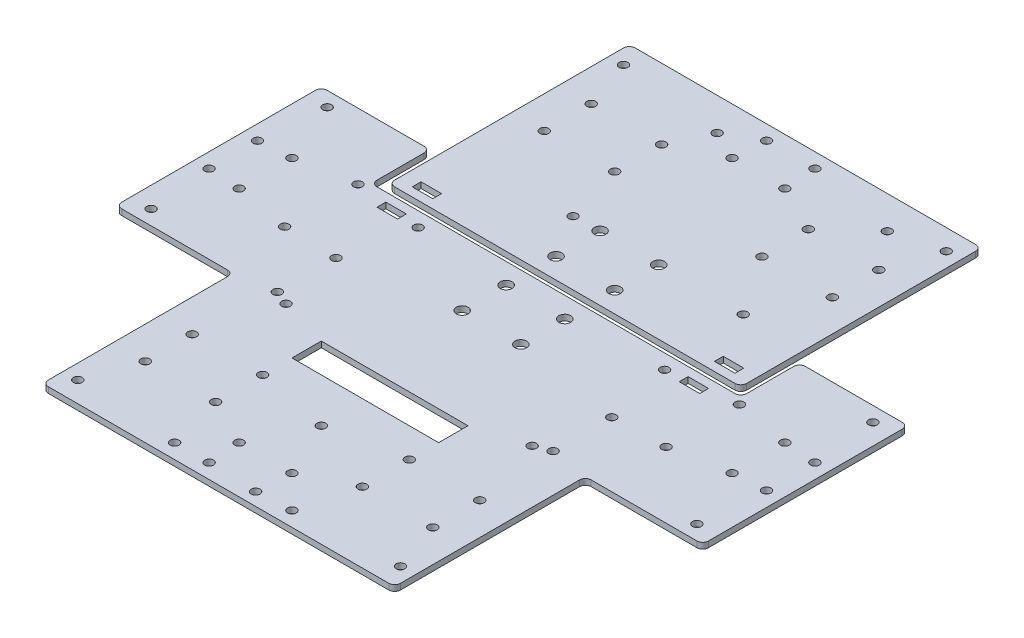
SolidWorks part; units mm, degrees
ref_plane "前视基准面" through (0, 0, 0) normal (0, 0, 1) x (1, 0, 0)
ref_plane "上视基准面" through (0, 0, 0) normal (0, 1, 0) x (1, 0, 0)
ref_plane "右视基准面" through (0, 0, 0) normal (1, 0, 0) x (0, 0, -1)
sketch "草图1" plane through (0, 0, 0) normal (0, 1, 0) x (1, 0, 0)
  line L1 (-97.8773, 105.9195) -> (102.1227, 105.9195)
  line L2 (-97.8773, 105.9195) -> (-97.8773, -94.0805)
  line L3 (-97.8773, -94.0805) -> (102.1227, -94.0805)
  line L4 (102.1227, 105.9195) -> (102.1227, -94.0805)
  dimension "D1" = 200
  dimension "D2" = 200
extrude "底板" add sketch "草图1" along normal blind 2
sketch "草图2" plane through (0, 2, 0) normal (0, 1, 0) x (1, 0, 0)
  line L1 (-97.8773, 105.9195) -> (-57.8773, 105.9195)
  line L2 (-97.8773, 105.9195) -> (-97.8773, 40.9195)
  line L3 (-97.8773, 40.9195) -> (-57.8773, 40.9195)
  line L4 (-57.8773, 105.9195) -> (-57.8773, 40.9195)
  line L9 (102.1227, 105.9195) -> (62.1227, 105.9195)
  line L10 (102.1227, 105.9195) -> (102.1227, 40.9195)
  line L11 (102.1227, 40.9195) -> (62.1227, 40.9195)
  line L12 (62.1227, 105.9195) -> (62.1227, 40.9195)
  line L13 (102.1227, -94.0805) -> (62.1227, -94.0805)
  line L14 (102.1227, -94.0805) -> (102.1227, -29.0805)
  line L15 (102.1227, -29.0805) -> (62.1227, -29.0805)
  line L16 (62.1227, -94.0805) -> (62.1227, -29.0805)
  line L17 (-97.8773, -94.0805) -> (-57.8773, -94.0805)
  line L18 (-97.8773, -94.0805) -> (-97.8773, -29.0805)
  line L19 (-97.8773, -29.0805) -> (-57.8773, -29.0805)
  line L20 (-57.8773, -94.0805) -> (-57.8773, -29.0805)
  dimension "D1" = 65
  dimension "D2" = 40
extrude "麦轮挖空" cut sketch "草图2" against normal blind 2
sketch "草图3" plane through (0, 2, 0) normal (0, 1, 0) x (1, 0, 0)
  line L0 (62.1227, 105.9195) -> (62.1227, 40.9195) construction
  line L1 (62.1227, 105.9195) -> (-57.8773, 105.9195) construction
  line L3 (-57.8773, 40.9195) -> (-57.8773, 105.9195) construction
  line L4 (-57.8773, -94.0805) -> (-57.8773, -29.0805) construction
  line L5 (-57.8773, -94.0805) -> (62.1227, -94.0805) construction
  line L6 (62.1227, -29.0805) -> (62.1227, -94.0805) construction
  circle A0 centre (-46.8773, 81.9195) radius 1.5
  circle A1 centre (-22.8773, 81.9195) radius 1.5
  circle A2 centre (-46.8773, 65.9195) radius 1.5
  circle A3 centre (-22.8773, 65.9195) radius 1.5
  circle A4 centre (-46.8773, -54.0805) radius 1.5
  circle A5 centre (-22.8773, -54.0805) radius 1.5
  circle A6 centre (-46.8773, -70.0805) radius 1.5
  circle A7 centre (-22.8773, -70.0805) radius 1.5
  circle A8 centre (27.1227, -54.0805) radius 1.5
  circle A9 centre (51.1227, -54.0805) radius 1.5
  circle A10 centre (27.1227, -70.0805) radius 1.5
  circle A11 centre (51.1227, -70.0805) radius 1.5
  circle A12 centre (27.1227, 81.9195) radius 1.5
  circle A13 centre (51.1227, 81.9195) radius 1.5
  circle A14 centre (27.311, 65.9206) radius 1.5
  circle A15 centre (51.311, 65.9206) radius 1.5
  dimension "D1" = 24
  dimension "D2" = 16
  dimension "D3" = 16
  dimension "D4" = 24
  dimension "D5" = 11
  dimension "D6" = 24
  dimension "D7" = 16
  dimension "D8" = 16
  dimension "D9" = 11
  dimension "D10" = 24
  dimension "D11" = 24
  dimension "D12" = 16
  dimension "D13" = 16
  dimension "D14" = 11
  dimension "D15" = 24
  dimension "D16" = 24
  dimension "D17" = 24
  dimension "D18" = 16
  dimension "D19" = 16
  dimension "D20" = 24
  dimension "D21" = 11
  dimension "D22" = 24
  dimension "D23" = 24
  dimension "D24" = 24
extrude "电机支架钻孔" cut sketch "草图3" against normal blind 2
sketch "草图4" plane through (0, 2, 0) normal (0, 1, 0) x (1, 0, 0)
  line L0 (62.1227, 105.9195) -> (-57.8773, 105.9195) construction
  line L1 (-97.8773, 40.9195) -> (-97.8773, -29.0805) construction
  line L2 (-57.8773, -94.0805) -> (62.1227, -94.0805) construction
  line L3 (102.1227, -29.0805) -> (102.1227, 40.9195) construction
  circle A0 centre (-6.8773, 89.9195) radius 1.5
  circle A1 centre (11.1227, 89.9195) radius 1.5
  circle A2 centre (-6.8773, -78.0805) radius 1.5
  circle A3 centre (11.1227, -78.0805) radius 1.5
  circle A4 centre (-81.8773, 14.9195) radius 1.5
  circle A5 centre (-81.8773, -3.0805) radius 1.5
  circle A6 centre (86.1227, 14.9195) radius 1.5
  circle A7 centre (86.1227, -3.0805) radius 1.5
  point P4 (-97.8773, 5.9195)
  point P9 (2.1227, 105.9195)
  point P14 (2.1227, -94.0805)
  point P29 (102.1227, 5.9195)
  dimension "D1" = 18
  dimension "D8" = 18
  dimension "D2" = 16
  dimension "D3" = 16
  dimension "D4" = 9
  dimension "D5" = 18
  dimension "D6" = 9
  dimension "D7" = 16
  dimension "D9" = 16
  dimension "D10" = 16
  dimension "D11" = 9
  dimension "D12" = 18
  dimension "D13" = 16
  dimension "D14" = 9
  dimension "D15" = 16
extrude "巡线钻孔" cut sketch "草图4" against normal blind 2
sketch "草图5" plane through (0, 2, 0) normal (0, 1, 0) x (1, 0, 0)
  line L0 (-57.8773, -94.0805) -> (62.1227, -94.0805) construction
  line L1 (-57.8773, -94.0805) -> (-57.8773, -29.0805) construction
  line L2 (62.1227, -29.0805) -> (62.1227, -94.0805) construction
  line L3 (62.1227, 105.9195) -> (62.1227, 40.9195) construction
  line L4 (62.1227, 105.9195) -> (-57.8773, 105.9195) construction
  line L7 (-57.8773, 40.9195) -> (-57.8773, 105.9195) construction
  line L8 (-97.8773, 40.9195) -> (-57.8773, 40.9195) construction
  line L9 (-97.8773, 40.9195) -> (-97.8773, -29.0805) construction
  line L10 (102.1227, -29.0805) -> (102.1227, 40.9195) construction
  line L11 (62.1227, 40.9195) -> (102.1227, 40.9195) construction
  line L12 (102.1227, -29.0805) -> (62.1227, -29.0805) construction
  line L13 (-57.8773, -29.0805) -> (-97.8773, -29.0805) construction
  circle A0 centre (-52.8773, -87.0805) radius 1.5
  circle A1 centre (57.1227, -87.0805) radius 1.5
  circle A2 centre (57.1227, 98.9195) radius 1.5
  circle A3 centre (-52.8773, 98.9195) radius 1.5
  circle A4 centre (-90.8773, 35.9195) radius 1.5
  circle A5 centre (-90.8773, -24.0805) radius 1.5
  circle A6 centre (95.1227, 35.9195) radius 1.5
  circle A7 centre (95.1227, -24.0805) radius 1.5
  dimension "D1" = 7
  dimension "D5" = 5
  dimension "D7" = 7
  dimension "D9" = 5
  dimension "D17" = 3
  dimension "D2" = 5
  dimension "D3" = 7
  dimension "D4" = 5
  dimension "D6" = 7
  dimension "D8" = 5
  dimension "D10" = 7
  dimension "D11" = 7
  dimension "D12" = 7
  dimension "D13" = 7
  dimension "D14" = 5
  dimension "D15" = 5
  dimension "D16" = 5
extrude "保险杠支架钻孔" cut sketch "草图5" against normal blind 10
sketch "草图7" plane through (0, 2, 0) normal (0, 1, 0) x (1, 0, 0)
  line L0 (62.1227, 105.9195) -> (-57.8773, 105.9195) construction
  circle A0 centre (-7.8773, 45.9195) radius 2
  circle A1 centre (-7.8773, 30.9195) radius 2
  circle A2 centre (-7.8773, 13.9195) radius 2
  circle A3 centre (-7.8773, -1.0805) radius 2
  circle A4 centre (12.1227, 45.9195) radius 2
  circle A5 centre (12.1227, 30.9195) radius 2
  circle A6 centre (12.1227, 13.9195) radius 2
  circle A7 centre (12.1227, -1.0805) radius 2
  point P19 (2.1227, 105.9195)
  dimension "D1" = 20
  dimension "D5" = 15
  dimension "D6" = 15
  dimension "D7" = 17
  dimension "D8" = 17
  dimension "D9" = 4
  dimension "D10" = 15
  dimension "D11" = 15
  dimension "D2" = 20
  dimension "D3" = 20
  dimension "D4" = 20
  dimension "D12" = 10
  dimension "D13" = 60
extrude "悬挂钻孔" cut sketch "草图7" against normal blind 10
sketch "草图8" plane through (0, 2, 0) normal (0, 1, 0) x (1, 0, 0)
  line L0 (-57.8773, 40.9195) -> (-57.8773, 23.9195)
  line L1 (-57.8773, 23.9195) -> (62.1227, 23.9195)
  line L2 (62.1227, 23.9195) -> (62.1227, 40.9195)
  line L3 (-57.8773, 40.9195) -> (-60.8773, 40.9195)
  line L4 (-97.8773, 40.9195) -> (-57.8773, 40.9195) construction
  line L5 (-60.8773, 40.9195) -> (-60.8773, 20.9195)
  line L6 (-60.8773, 20.9195) -> (65.1227, 20.9195)
  line L7 (65.1227, 20.9195) -> (65.1227, 40.9195)
  line L8 (62.1227, 40.9195) -> (102.1227, 40.9195) construction
  line L9 (65.1227, 40.9195) -> (62.1227, 40.9195)
  circle A0 centre (-7.8773, 30.9195) radius 2 construction
  dimension "D1" = 7
  dimension "D2" = 3
  dimension "D3" = 3
  dimension "D4" = 3
extrude "悬挂开槽" cut sketch "草图8" against normal blind 10
fillet "主板圆角" radius 2 12 edges at (-97.8773, 1, -40.9195) (-60.8773, 1, -40.9195) (-60.8773, 1, -20.9195) (65.1227, 1, -20.9195) (65.1227, 1, -40.9195) (102.1227, 1, -40.9195) (102.1227, 1, 29.0805) (62.1227, 1, 29.0805) (62.1227, 1, 94.0805) (-57.8773, 1, 94.0805) (-57.8773, 1, 29.0805) (-97.8773, 1, 29.0805)
fillet "小板圆角" radius 2 4 edges at (62.1227, 1, -23.9195) (-57.8773, 1, -23.9195) (-57.8773, 1, -105.9195) (62.1227, 1, -105.9195)
sketch "草图11" plane through (0, 2, 0) normal (0, 1, 0) x (1, 0, 0)
  line L0 (-55.8773, -94.0805) -> (60.1227, -94.0805) construction
  line L2 (62.1227, -31.0805) -> (62.1227, -92.0805) construction
  line L3 (-57.8773, -92.0805) -> (-57.8773, -31.0805) construction
  circle A0 centre (-17.8773, -89.0805) radius 1.5
  circle A1 centre (22.1227, -89.0805) radius 1.5
  circle A2 centre (2.1227, -59.0805) radius 1.5
  dimension "D1" = 5
  dimension "D3" = 40
  dimension "D5" = 35
  dimension "D6" = 60
  dimension "D2" = 5
  dimension "D4" = 40
extrude "切除-拉伸1" cut sketch "草图11" against normal blind 10
sketch "草图13" plane through (0, 2, 0) normal (0, 1, 0) x (1, 0, 0)
  line L0 (-97.8773, 38.9195) -> (-97.8773, -27.0805) construction
  line L1 (-58.8773, 20.9195) -> (63.1227, 20.9195) construction
  circle A0 centre (-39.8773, 15.9195) radius 1.5
  circle A1 centre (44.1227, 15.9195) radius 1.5
  circle A2 centre (-39.8773, -29.0805) radius 1.5
  circle A3 centre (43.9828, -29.0805) radius 1.5
  dimension "D1" = 84
  dimension "D2" = 45
  dimension "D3" = 45
  dimension "D4" = 58
  dimension "D5" = 5
extrude "切除-拉伸3" cut sketch "草图13" against normal blind 10
sketch "草图14" plane through (0, 2, 0) normal (0, 1, 0) x (1, 0, 0)
  line L0 (60.1227, 105.9195) -> (-55.8773, 105.9195) construction
  line L1 (-97.8773, 38.9195) -> (-97.8773, -27.0805) construction
  line L2 (102.1227, -27.0805) -> (102.1227, 38.9195) construction
  line L3 (-55.8773, -94.0805) -> (60.1227, -94.0805) construction
  circle A0 centre (-6.1273, 100.9195) radius 1.5
  circle A1 centre (10.3727, 100.9195) radius 1.5
  circle A4 centre (-6.1145, -89.0805) radius 1.5
  circle A5 centre (10.3727, -89.7286) radius 1.5
  circle A6 centre (-92.8773, 14.1695) radius 1.5
  circle A7 centre (-92.8773, -2.3305) radius 1.5
  circle A8 centre (97.1227, 14.1695) radius 1.5
  circle A9 centre (97.1227, -2.3305) radius 1.5
  dimension "D1" = 3
  dimension "D2" = 3
  dimension "D5" = 5
  dimension "D8" = 3
  dimension "D9" = 3
  dimension "D10" = 91.75
  dimension "D12" = 3
  dimension "D13" = 3
  dimension "D14" = 16.5
  dimension "D15" = 5
  dimension "D16" = 91.75
  dimension "D17" = 16.5
  dimension "D18" = 5
  dimension "D3" = 16.5
  dimension "D4" = 0
  dimension "D6" = 91.75
  dimension "D7" = 16.5
  dimension "D11" = 5
  dimension "D19" = 91.75
extrude "切除-拉伸4" cut sketch "草图14" against normal blind 10
sketch "草图15" plane through (0, 2, 0) normal (0, 1, 0) x (1, 0, 0)
  line L1 (-97.8773, 38.9195) -> (-97.8773, -27.0805) construction
  line L2 (-58.8773, 20.9195) -> (63.1227, 20.9195) construction
  circle A0 centre (-44.8773, -7.0805) radius 1.5
  circle A1 centre (-44.8773, -27.0805) radius 1.5
  circle A2 centre (49.1227, -7.0805) radius 1.5
  circle A3 centre (49.1227, -27.0805) radius 1.5
  dimension "D1" = 94
  dimension "D3" = 94
  dimension "D4" = 20
  dimension "D5" = 53
  dimension "D2" = 20
  dimension "D6" = 28
extrude "切除-拉伸5" cut sketch "草图15" against normal blind 10
sketch "草图16" plane through (0, 2, 0) normal (0, 1, 0) x (1, 0, 0)
  line L0 (102.1227, -27.0805) -> (102.1227, 38.9195) construction
  circle A0 centre (-16.8273, 94.7651) radius 1.5
  circle A1 centre (41.1727, 94.7651) radius 1.5
  circle A2 centre (41.1727, 45.6651) radius 1.5
  circle A3 centre (-16.8273, 45.6651) radius 1.5
  dimension "D1" = 49.1
  dimension "D2" = 49.1
  dimension "D3" = 58
  dimension "D4" = 0
  dimension "D5" = 60.95
  dimension "D6" = 58
  dimension "D7" = 0
extrude "切除-拉伸6" cut sketch "草图16" against normal blind 10
sketch "草图17" plane through (0, 2, 0) normal (0, 1, 0) x (1, 0, 0)
  line L0 (-97.8773, 38.9195) -> (-97.8773, -27.0805) construction
  line L1 (-22.8773, -34.0805) -> (27.1227, -34.0805)
  line L2 (-22.8773, -34.0805) -> (-22.8773, -44.0805)
  line L3 (-22.8773, -44.0805) -> (27.1227, -44.0805)
  line L4 (27.1227, -34.0805) -> (27.1227, -44.0805)
  line L5 (-55.8773, -94.0805) -> (60.1227, -94.0805) construction
  dimension "D1" = 75
  dimension "D2" = 10
  dimension "D3" = 50
  dimension "D4" = 50
extrude "切除-拉伸7" cut sketch "草图17" against normal blind 10
sketch "草图18" plane through (0, 0, 0) normal (0, -1, 0) x (1, 0, 0)
  line L0 (60.1227, -23.9195) -> (-55.8773, -23.9195) construction
  line L1 (57.1227, -29.9195) -> (50.1227, -29.9195)
  line L2 (57.1227, -29.9195) -> (57.1227, -26.9195)
  line L3 (57.1227, -26.9195) -> (50.1227, -26.9195)
  line L4 (50.1227, -29.9195) -> (50.1227, -26.9195)
  line L5 (57.1227, -17.9195) -> (50.1227, -17.9195)
  line L6 (57.1227, -17.9195) -> (57.1227, -14.9195)
  line L7 (57.1227, -14.9195) -> (50.1227, -14.9195)
  line L8 (50.1227, -17.9195) -> (50.1227, -14.9195)
  line L9 (-58.8773, -20.9195) -> (63.1227, -20.9195) construction
  line L10 (62.1227, -103.9195) -> (62.1227, -25.9195) construction
  line L12 (-45.8773, -29.9195) -> (-52.8773, -29.9195)
  line L13 (-45.8773, -29.9195) -> (-45.8773, -26.9195)
  line L14 (-45.8773, -26.9195) -> (-52.8773, -26.9195)
  line L15 (-52.8773, -29.9195) -> (-52.8773, -26.9195)
  line L16 (-45.8773, -17.9195) -> (-52.8773, -17.9195)
  line L17 (-45.8773, -17.9195) -> (-45.8773, -14.9195)
  line L18 (-45.8773, -14.9195) -> (-52.8773, -14.9195)
  line L19 (-52.8773, -17.9195) -> (-52.8773, -14.9195)
  line L20 (-57.8773, -25.9195) -> (-57.8773, -103.9195) construction
  dimension "D1" = 3
  dimension "D2" = 7
  dimension "D3" = 7
  dimension "D4" = 3
  dimension "D5" = 3
  dimension "D6" = 3
  dimension "D7" = 5
  dimension "D8" = 5
  dimension "D9" = 7
  dimension "D10" = 3
  dimension "D11" = 3
  dimension "D12" = 7
  dimension "D13" = 5
  dimension "D14" = 5
  dimension "D15" = 3
  dimension "D16" = 3
extrude "切除-拉伸8" cut sketch "草图18" against normal blind 10
sketch "草图19" plane through (0, 0, 0) normal (0, -1, 0) x (1, 0, 0)
  line L0 (60.1227, -105.9195) -> (-55.8773, -105.9195) construction
  line L1 (102.1227, 27.0805) -> (102.1227, -38.9195) construction
  line L2 (-97.8773, -38.9195) -> (-97.8773, 27.0805) construction
  circle A0 centre (67.1227, -18.4195) radius 1.5
  circle A1 centre (67.1227, 6.5805) radius 1.5
  circle A2 centre (-62.8773, -18.4195) radius 1.5
  circle A3 centre (-62.8773, 6.5805) radius 1.5
  dimension "D1" = 25
  dimension "D2" = 87.5
  dimension "D3" = 35
  dimension "D4" = 3
  dimension "D5" = 3
  dimension "D6" = 3
  dimension "D7" = 3
  dimension "D8" = 25
  dimension "D9" = 87.5
  dimension "D10" = 35
extrude "切除-拉伸9" cut sketch "草图19" against normal blind 10
